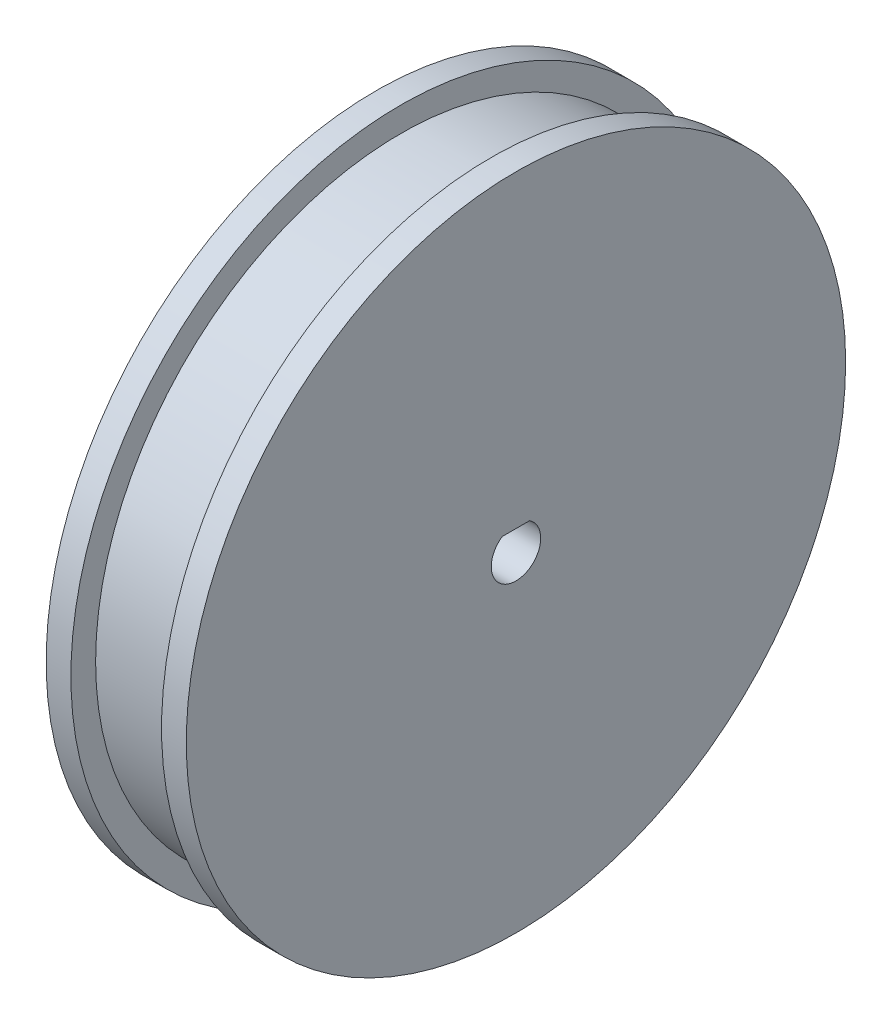
SolidWorks part; units mm, degrees
ref_plane "Plan de face" through (0, 0, 0) normal (0, 0, 1) x (1, 0, 0)
ref_plane "Plan de dessus" through (0, 0, 0) normal (0, 1, 0) x (1, 0, 0)
ref_plane "Plan de droite" through (0, 0, 0) normal (1, 0, 0) x (0, 0, -1)
sketch "Esquisse1" plane through (0, 0, 0) normal (1, 0, 0) x (0, 0, -1)
  line L0 (-1.6583, 2.5) -> (1.6583, 2.5)
  line L1 (0, 0) -> (0, 4.7784) construction
  arc A0 (-1.6583, 2.5) -> (1.6583, 2.5) centre (0, 0) ccw
  circle A1 centre (0, 0) radius 40
  point P6 (0, 3)
  dimension "D1" = 6
  dimension "D3" = 80
  dimension "D2" = 0.5
extrude "BASE" add sketch "Esquisse1" along normal blind 12 and the other way blind 5
sketch "Esquisse4" plane through (0, 0, 0) normal (1, 0, 0) x (0, 0, -1)
  circle A0 centre (0, 0) radius 37
  circle A1 centre (0, 0) radius 40
  dimension "D1" = 3
extrude "VIDE PNEU" cut sketch "Esquisse4" against normal blind 2 and the other way blind 9
